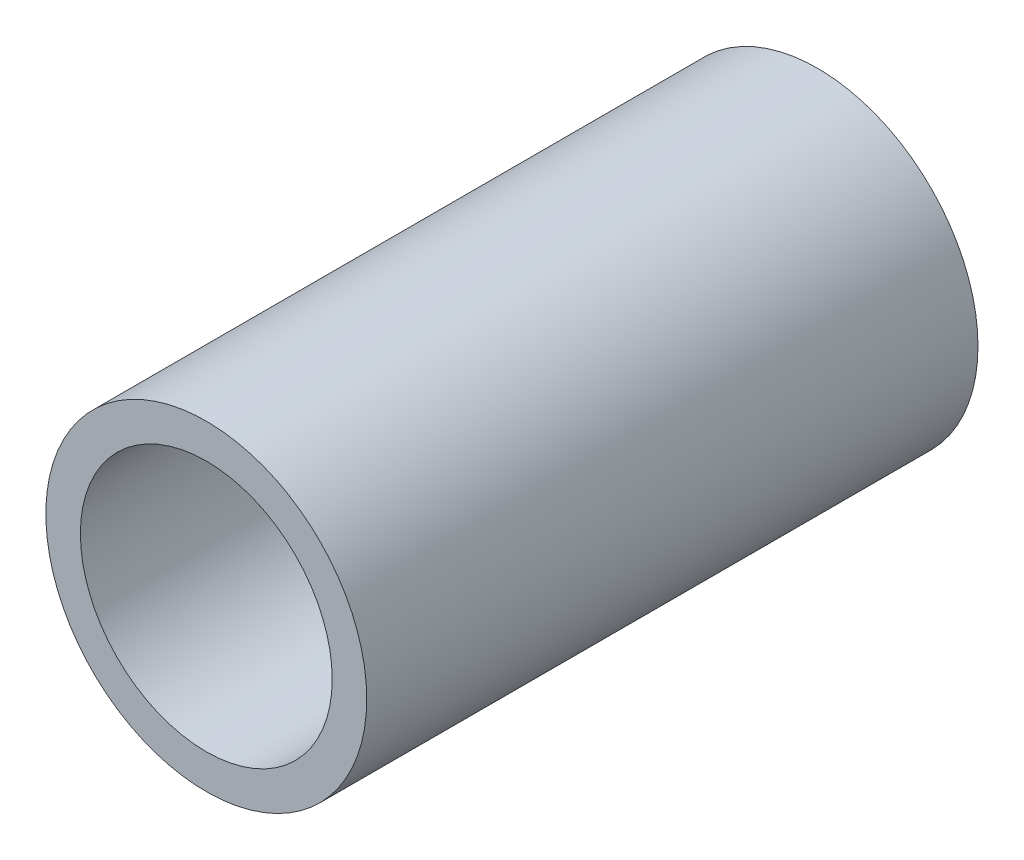
SolidWorks part; units mm, degrees
ref_plane "Front Plane" through (0, 0, 0) normal (0, 0, 1) x (1, 0, 0)
ref_plane "Top Plane" through (0, 0, 0) normal (0, 1, 0) x (1, 0, 0)
ref_plane "Right Plane" through (0, 0, 0) normal (1, 0, 0) x (0, 0, -1)
sketch "Sketch1" plane through (0, 0, 0) normal (0, 0, 1) x (1, 0, 0)
  circle A0 centre (0, 0) radius 10.4648
  circle A1 centre (0, 0) radius 13.335
  dimension "D1" = 20.9296
  dimension "D2" = 26.67
extrude "Boss-Extrude1" add sketch "Sketch1" along normal mid plane 50.8
